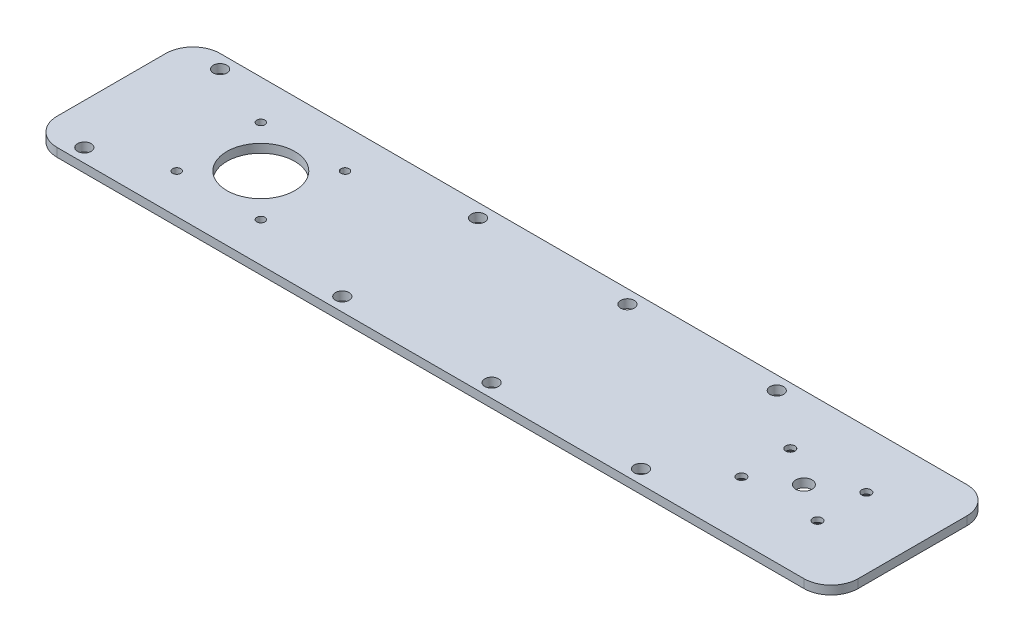
SolidWorks part; units mm, degrees
ref_plane "Front Plane" through (0, 0, 0) normal (0, 0, 1) x (1, 0, 0)
ref_plane "Top Plane" through (0, 0, 0) normal (0, 1, 0) x (1, 0, 0)
ref_plane "Right Plane" through (0, 0, 0) normal (1, 0, 0) x (0, 0, -1)
sketch "Sketch1" plane through (0, 0, 0) normal (0, 1, 0) x (1, 0, 0)
  line L0 (-55, 0) -> (0, 0) construction
  line L1 (-55, 30) -> (240, 30)
  line L2 (-55, 30) -> (-55, -30)
  line L3 (-55, -30) -> (240, -30)
  line L4 (240, 30) -> (240, -30)
  point P7 (200, 0)
  dimension "D1" = 60
  dimension "D2" = 55
  dimension "D3" = 200
  dimension "D4" = 40
extrude "Boss-Extrude1" add sketch "Sketch1" along normal blind 3.175
fillet "Fillet1" radius 10 4 edges at (-55, 1.5875, 30) (-55, 1.5875, -30) (240, 1.5875, 30) (240, 1.5875, -30)
hole_wizard "Ø3.0mm Dowel Hole1" positions "Sketch3" profile "Sketch5" hole size "Ø3.0" standard "DIN" end condition up to next
sketch "Sketch3" plane through (0, 3.175, 0) normal (0, 1, 0) x (1, 0, 0)
  point P0 (-15.5, 15.5)
  point P29 (15.5, 15.5)
  point P30 (15.5, -15.5)
  point P31 (-15.5, -15.5)
  dimension "D1" = 15.5
  dimension "D2" = 15.5
  dimension "D5" = 31
  dimension "D6" = 31
  dimension "D3" = 2
  dimension "D4" = 2
sketch "Sketch5" plane through (-15.5, 3.175, -15.5) normal (1, 0, 0) x (0, 0, 1)
  line L0 (0, 0) -> (0, 3.175)
  line L1 (0, 3.175) -> (1.5, 3.175)
  line L2 (1.5, 3.175) -> (1.5, 0)
  line L5 (1.5, 0) -> (0, 0)
  line L11 (0, -6.35) -> (0, 107.95) construction
  dimension "Thru Hole Dia." = 3
  dimension "Thru Hole Depth" = 3.175
sketch "Sketch6" plane through (0, 3.175, 0) normal (0, 1, 0) x (1, 0, 0)
  circle A0 centre (0, 0) radius 12.5
  dimension "D1" = 25
extrude "Cut-Extrude1" cut sketch "Sketch6" against normal through all
hole_wizard "Ø6.0mm Dowel Hole1" positions "Sketch7" profile "Sketch8" hole size "Ø6.0" standard "DIN" end condition up to next
sketch "Sketch7" plane through (0, 3.175, 0) normal (0, 1, 0) x (1, 0, 0)
  point P0 (200, 0)
  dimension "D1" = 200
sketch "Sketch8" plane through (200, 3.175, 0) normal (1, 0, 0) x (0, 0, 1)
  line L0 (0, 0) -> (0, 3.175)
  line L1 (0, 3.175) -> (3, 3.175)
  line L2 (3, 3.175) -> (3, 0)
  line L5 (3, 0) -> (0, 0)
  line L11 (0, -6.35) -> (0, 107.95) construction
  dimension "Thru Hole Dia." = 6
  dimension "Thru Hole Depth" = 3.175
hole_wizard "CSK for M3 Flat Head Machine Screw1" positions "Sketch10" profile "Sketch11" countersink size "M3" standard "ANSI Metric" end condition up to next
sketch "Sketch10" plane through (0, 0, 0) normal (0, -1, 0) x (-1, 0, 0)
  line L0 (-214, 9) -> (-186, 9) construction
  circle A0 centre (-200, 0) radius 3 construction
  point P0 (-214, 9)
  point P7 (-186, 9)
  point P8 (-186, -9)
  point P9 (-214, -9)
  dimension "D4" = 14
  dimension "D5" = 9
  dimension "D3" = 28
  dimension "D6" = 18
  dimension "D1" = 2
  dimension "D2" = 2
sketch "Sketch11" plane through (214, 0, -9) normal (1, 0, 0) x (0, 0, -1)
  line L0 (0, 0) -> (0, 3.175)
  line L1 (0, 3.175) -> (1.7, 3.175)
  line L2 (1.7, 3.175) -> (1.7, 1.45)
  line L3 (1.7, 1.45) -> (3.15, 0)
  line L5 (3.15, 0) -> (0, 0)
  line L6 (-1.7, 1.45) -> (-3.15, 0) construction
  line L11 (0, -6.35) -> (0, 107.95) construction
  dimension "Thru Hole Dia." = 3.4
  dimension "Thru Hole Depth" = 3.175
  dimension "Near C'Sink Dia." = 6.3
  dimension "Near C'Sink Angle" = 90
hole_wizard "Ø5.0mm Dowel Hole1" positions "Sketch12" profile "Sketch13" hole size "Ø5.0" standard "DIN" end condition through all
sketch "Sketch12" plane through (0, 3.175, 0) normal (0, 1, 0) x (1, 0, 0)
  line L0 (-45, -30) -> (230, -30) construction
  line L1 (55, -25) -> (110, -25) construction
  line L2 (-55, 0) -> (240, 0) construction
  line L3 (-55, 20) -> (-55, -20) construction
  line L4 (240, -20) -> (240, 20) construction
  point P0 (55, -25)
  point P14 (110, -25)
  point P15 (165, -25)
  point P25 (165, 25)
  point P26 (110, 25)
  point P27 (55, 25)
  point P28 (-40, -25)
  point P31 (-40, 25)
  dimension "D1" = 5
  dimension "D2" = 55
  dimension "D4" = 55
  dimension "D5" = 15
  dimension "D3" = 3
sketch "Sketch13" plane through (55, 3.175, 25) normal (1, 0, 0) x (0, 0, 1)
  line L0 (0, 0) -> (0, 3.175)
  line L1 (0, 3.175) -> (2.5, 3.175)
  line L2 (2.5, 3.175) -> (2.5, 0)
  line L5 (2.5, 0) -> (0, 0)
  line L11 (0, -6.35) -> (0, 107.95) construction
  dimension "Thru Hole Dia." = 5
  dimension "Thru Hole Depth" = 3.175
equation "\"Pivot to Pivot Dist\"= 200"
equation "\"D3@Sketch1\"=\"Pivot to Pivot Dist\""
equation "\"D1@Sketch7\"=\"Pivot to Pivot Dist\""
